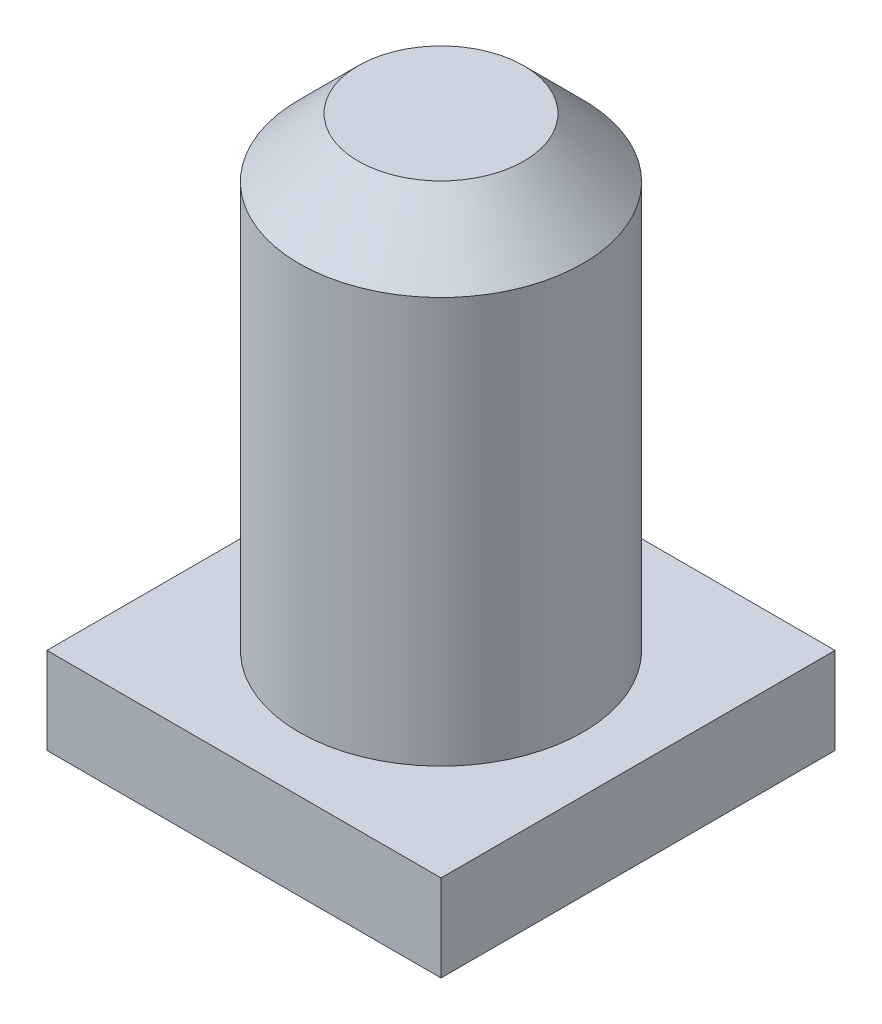
SolidWorks part; units mm, degrees
ref_plane "Front" through (0, 0, 0) normal (0, 0, 1) x (1, 0, 0)
ref_plane "Top" through (0, 0, 0) normal (0, 1, 0) x (1, 0, 0)
ref_plane "Right" through (0, 0, 0) normal (1, 0, 0) x (0, 0, -1)
sketch "Sketch1" plane through (0, 0, 0) normal (0, 1, 0) x (1, 0, 0)
  circle A0 centre (0, 0) radius 1.8
  dimension "D1" = 3.6
extrude "Boss-Extrude1" add sketch "Sketch1" along normal blind 7
sketch "Sketch3" plane through (0, 0, 0) normal (0, -1, 0) x (1, 0, 0)
  line L1 (-2.5, -2.5) -> (2.5, -2.5)
  line L2 (-2.5, -2.5) -> (-2.5, 2.5)
  line L3 (-2.5, 2.5) -> (2.5, 2.5)
  line L4 (2.5, -2.5) -> (2.5, 2.5)
  line L5 (-2.5, -2.5) -> (2.5, 2.5) construction
  line L6 (-2.5, 2.5) -> (2.5, -2.5) construction
  point P0 (0, 0)
  dimension "D1" = 5
extrude "Boss-Extrude2" add sketch "Sketch3" against normal blind 1.1
chamfer "Chamfer1" distance 0.75 angle 45 1 edges at (0, 7, 1.8)
